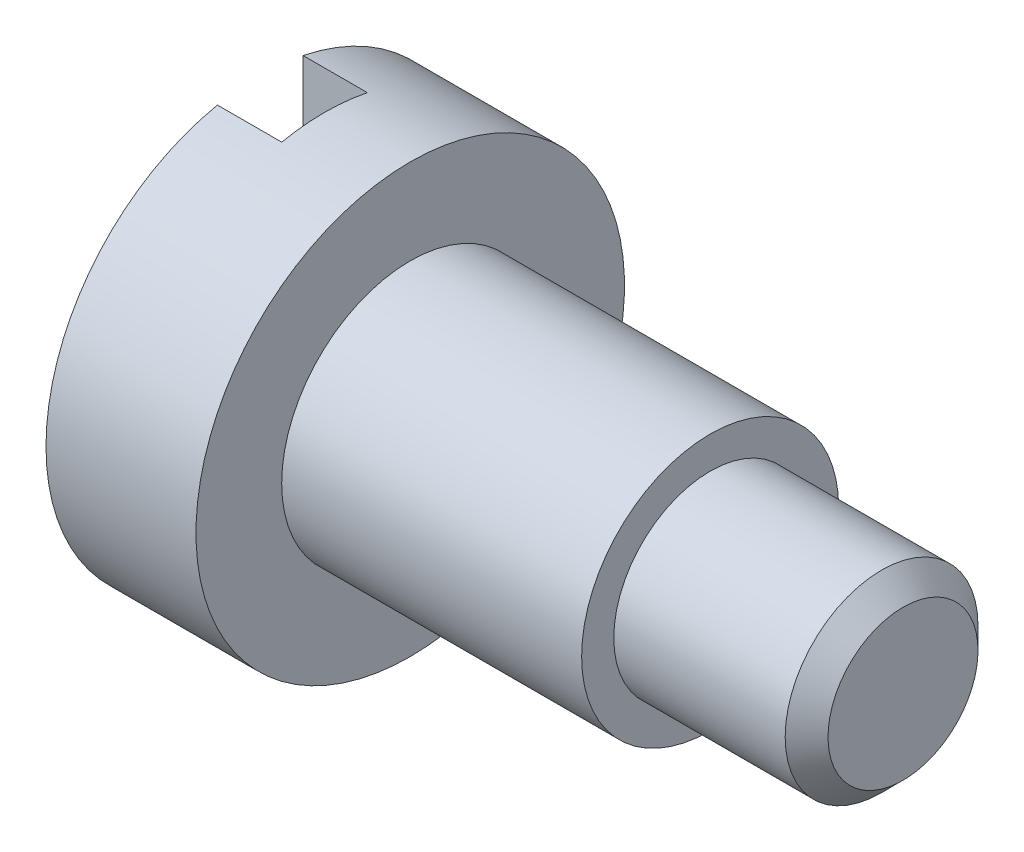
SolidWorks part; units mm, degrees
ref_plane "Plan de face" through (0, 0, 0) normal (0, 0, 1) x (1, 0, 0)
ref_plane "Plan de dessus" through (0, 0, 0) normal (0, 1, 0) x (1, 0, 0)
ref_plane "Plan de droite" through (0, 0, 0) normal (1, 0, 0) x (0, 0, -1)
sketch "Esquisse1" plane through (0, 0, 0) normal (0, 0, 1) x (1, 0, 0)
  line L0 (0, 0) -> (0, 5)
  line L1 (0, 5) -> (3.5, 5)
  line L2 (3.5, 5) -> (3.5, 3)
  line L3 (3.5, 3) -> (10.5, 3)
  line L4 (10.5, 3) -> (10.5, 2.25)
  line L5 (10.5, 2.25) -> (14.5, 2.25)
  line L6 (14.5, 2.25) -> (15, 1.75)
  line L7 (15, 1.75) -> (15, 0)
  line L8 (15, 0) -> (0, 0)
  dimension "D1" = 3.5
  dimension "D2" = 7
  dimension "D3" = 5
  dimension "D4" = 4.5
  dimension "D5" = 2.25
  dimension "D6" = 45
  dimension "D7" = 0.5
  dimension "D8" = 3
revolve "Révolution1" add sketch "Esquisse1" angle 360 about L8
sketch "Esquisse2" plane through (0, 0, 0) normal (-1, 0, 0) x (0, 0, 1)
  line L0 (0, 5) -> (0, -5) construction
  line L2 (-1, 6.365) -> (1, 6.365)
  line L3 (-1, 6.365) -> (-1, -6.4681)
  line L4 (-1, -6.4681) -> (1, -6.4681)
  line L5 (1, 6.365) -> (1, -6.4681)
  circle A0 centre (0, 0) radius 5 construction
  dimension "D1" = 1
  dimension "D2" = 1
extrude "Enlèv. mat.-Extru.1" cut sketch "Esquisse2" against normal blind 1.5
